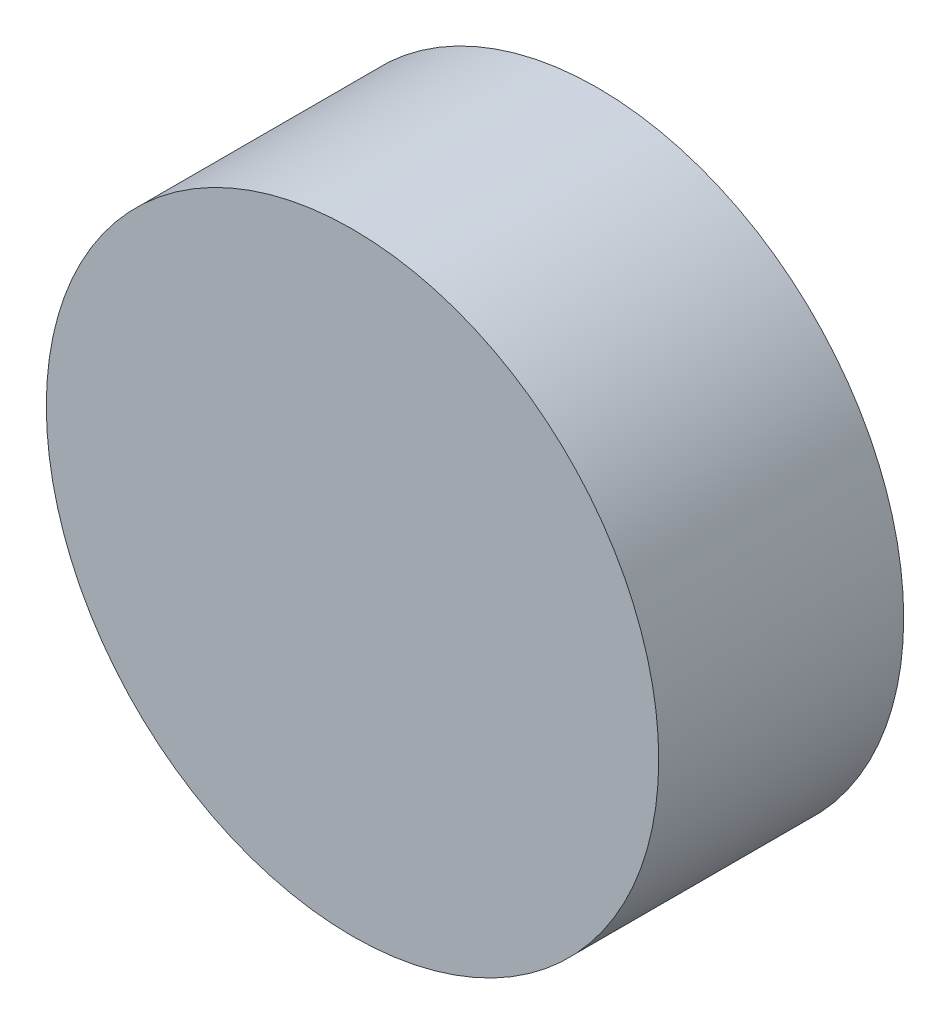
SolidWorks part; units mm, degrees
material "ABS"
ref_plane "Alzado" through (0, 0, 0) normal (0, 0, 1) x (1, 0, 0)
ref_plane "Planta" through (0, 0, 0) normal (0, 1, 0) x (1, 0, 0)
ref_plane "Vista lateral" through (0, 0, 0) normal (1, 0, 0) x (0, 0, -1)
sketch "Croquis1" plane through (0, 0, 0) normal (0, 0, 1) x (1, 0, 0)
  circle A0 centre (0, 0) radius 50
  dimension "D1" = 100
extrude "Saliente-Extruir1" add sketch "Croquis1" along normal blind 40
sketch "Croquis2" plane through (0, 0, 0) normal (0, 0, -1) x (-1, 0, 0)
  circle A0 centre (0, 0) radius 45
  circle A1 centre (0, 0) radius 32.5
  dimension "D1" = 90
  dimension "D2" = 65
extrude "Cortar-Extruir1" cut sketch "Croquis2" against normal blind 1.5
sketch "Croquis3" plane through (0, 0, 0) normal (0, 0, -1) x (-1, 0, 0)
  circle A0 centre (0, 0) radius 13
  circle A1 centre (0, 0) radius 5
  dimension "D1" = 26
  dimension "D2" = 10
extrude "Cortar-Extruir2" cut sketch "Croquis3" against normal blind 8
sketch "Croquis4" plane through (0, 0, 0) normal (0, 0, -1) x (-1, 0, 0)
  circle A0 centre (0, 0) radius 5
  dimension "D1" = 10
extrude "Cortar-Extruir3" cut sketch "Croquis4" against normal blind 10
